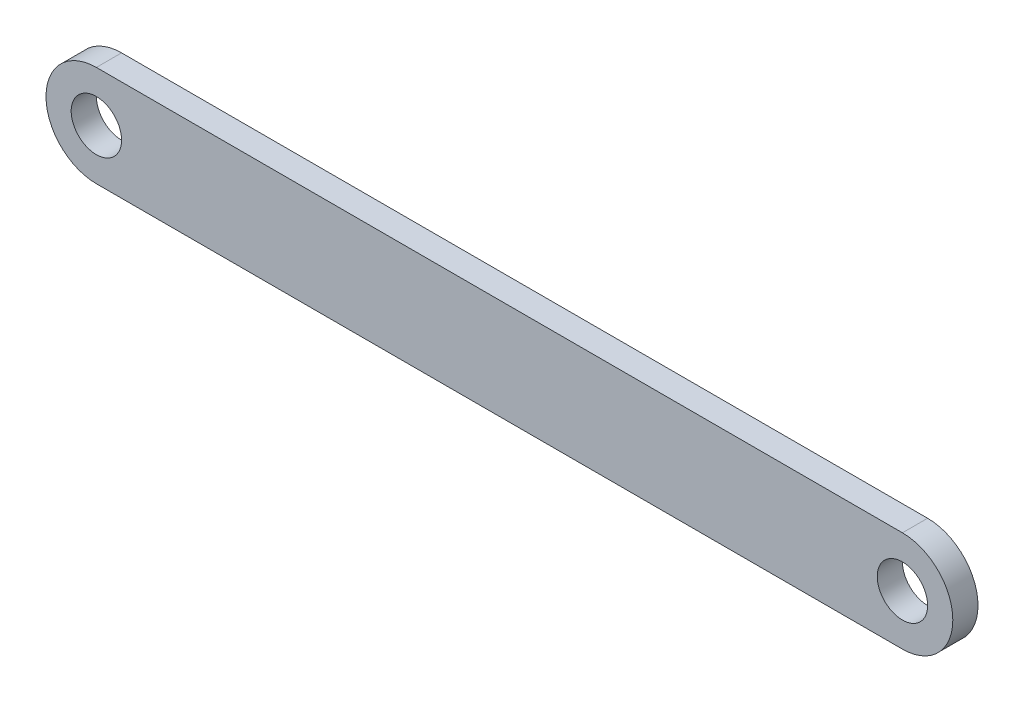
SolidWorks part; units mm, degrees
ref_plane "Ön Düzlem" through (0, 0, 0) normal (0, 0, 1) x (1, 0, 0)
ref_plane "Üst Düzlem" through (0, 0, 0) normal (0, 1, 0) x (1, 0, 0)
ref_plane "Sağ Düzlem" through (0, 0, 0) normal (1, 0, 0) x (0, 0, -1)
sketch "Çizim1" plane through (0, 0, 0) normal (0, 0, 1) x (1, 0, 0)
  line L0 (-38.6982, 2.8866) -> (121.3018, 2.8866) construction
  line L1 (-38.6982, 12.8866) -> (121.3018, 12.8866)
  line L2 (-38.6982, -7.1134) -> (121.3018, -7.1134)
  arc A0 (-38.6982, 12.8866) -> (-38.6982, -7.1134) centre (-38.6982, 2.8866) ccw
  arc A1 (121.3018, -7.1134) -> (121.3018, 12.8866) centre (121.3018, 2.8866) ccw
  circle A2 centre (-38.6982, 2.8866) radius 5
  circle A3 centre (121.3018, 2.8866) radius 5
  point P2 (41.3018, 2.8866)
  dimension "D1" = 160
  dimension "D2" = 20
extrude "Yükseklik-Ekstrüzyon1" add sketch "Çizim1" along normal blind 5
